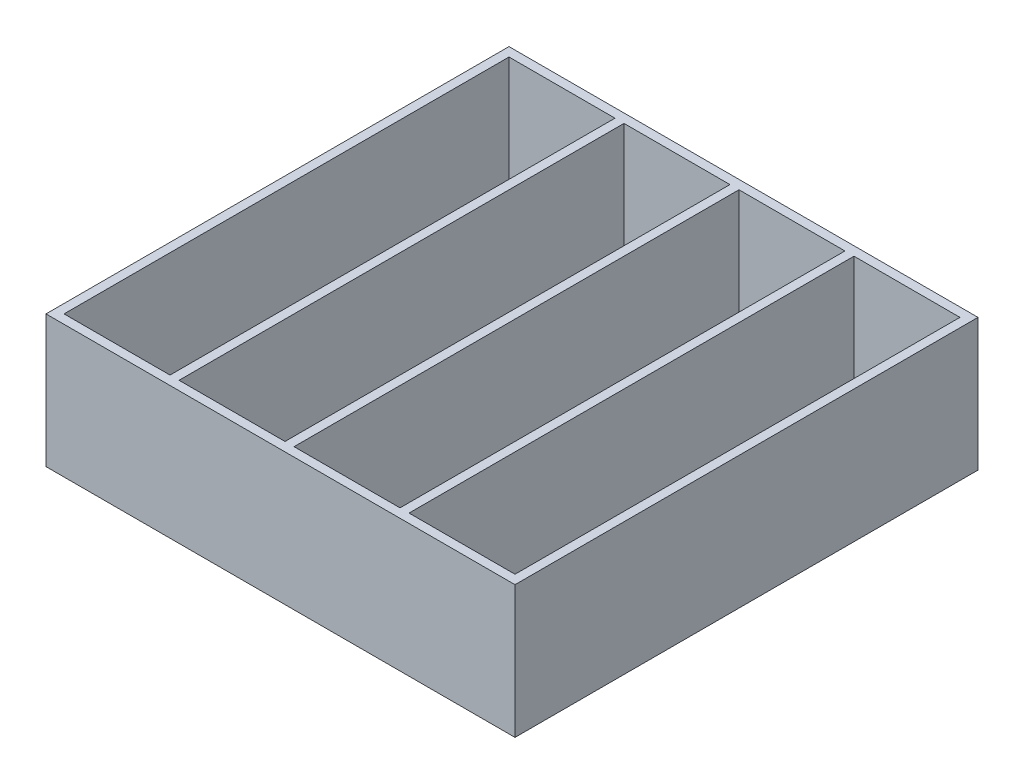
SolidWorks part; units mm, degrees
ref_plane "Front Plane" through (0, 0, 0) normal (0, 0, 1) x (1, 0, 0)
ref_plane "Top Plane" through (0, 0, 0) normal (0, 1, 0) x (1, 0, 0)
ref_plane "Right Plane" through (0, 0, 0) normal (1, 0, 0) x (0, 0, -1)
sketch "Sketch1" plane through (0, 0, 0) normal (0, 1, 0) x (1, 0, 0)
  line L1 (0, 0) -> (-78, 0)
  line L2 (0, 0) -> (0, -77)
  line L3 (0, -77) -> (-78, -77)
  line L4 (-78, 0) -> (-78, -77)
  dimension "D1" = 77
  dimension "D2" = 78
extrude "Boss-Extrude1" add sketch "Sketch1" along normal blind 22
ref_plane "Plane1" through (-78, 0, 77) normal (1, 0, 0) x (0, 0, -1)
sketch "Sketch3" plane through (0, 22, 0) normal (0, 1, 0) x (1, 0, 0)
  line L0 (-39.75, -1.5) -> (-39.75, -75.5)
  line L1 (-39.75, -75.5) -> (-20.625, -75.5)
  line L2 (-20.625, -75.5) -> (-20.625, -1.5)
  line L3 (-20.625, -1.5) -> (-19.125, -1.5)
  line L4 (-19.125, -1.5) -> (-19.125, -75.5)
  line L5 (-58.875, -75.5) -> (-58.875, -1.5)
  line L6 (-58.875, -1.5) -> (-57.375, -1.5)
  line L7 (-57.375, -1.5) -> (-57.375, -75.5)
  line L8 (-38.25, -75.5) -> (-38.25, -1.5)
  line L9 (-1.5, -75.5) -> (-1.5, -1.5)
  line L10 (-1.5, -1.5) -> (-76.5, -1.5)
  line L11 (-76.5, -1.5) -> (-76.5, -75.5)
  line L12 (-76.5, -75.5) -> (-1.5, -75.5)
  line L13 (-1.5, -75.5) -> (-1.5, -1.5)
  line L14 (-1.5, -1.5) -> (-76.5, -1.5)
  line L15 (-76.5, -1.5) -> (-76.5, -75.5)
  line L16 (-76.5, -75.5) -> (-1.5, -75.5)
  dimension "D2" = 17.625
  dimension "D3" = 1.5
  dimension "D4" = 1.5
  dimension "D5" = 1.5
  dimension "D6" = 17.625
  dimension "D7" = 17.625
  dimension "D8" = 17.625
  dimension "D1" = 1.5
extrude "Cut-Extrude1" cut sketch "Sketch3" against normal blind 20 contours L15 L16 L5 L14 | L7 L16 L0 L14 | L2 L14 L8 L1 | L4 L16 L13 L14
